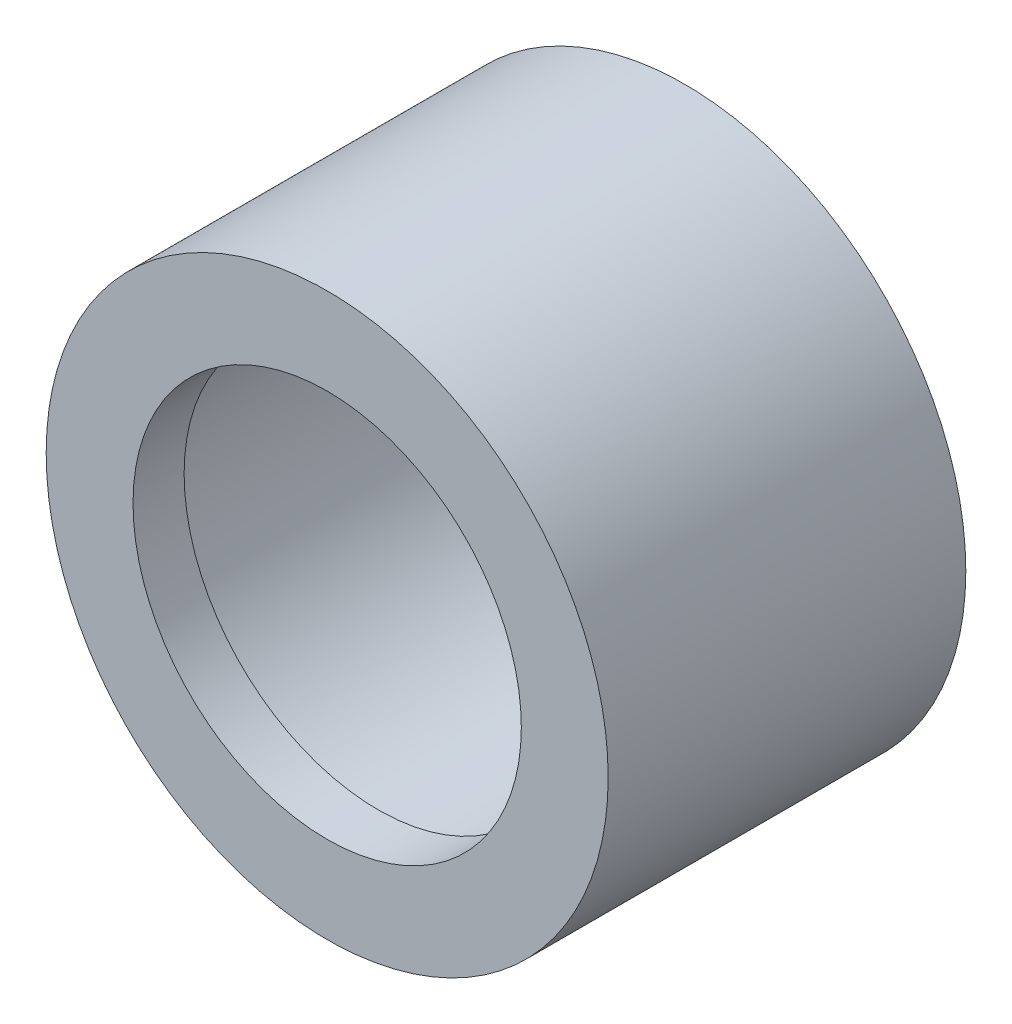
SolidWorks part; units mm, degrees
ref_plane "前视基准面" through (0, 0, 0) normal (0, 0, 1) x (1, 0, 0)
ref_plane "上视基准面" through (0, 0, 0) normal (0, 1, 0) x (1, 0, 0)
ref_plane "右视基准面" through (0, 0, 0) normal (1, 0, 0) x (0, 0, -1)
sketch "草图1" plane through (0, 0, 0) normal (0, 0, 1) x (1, 0, 0)
  circle A0 centre (0, 0) radius 27.5
  dimension "D1" = 55
extrude "拉伸1" add sketch "草图1" along normal blind 3
sketch "草图2" plane through (0, 0, 3) normal (0, 0, 1) x (1, 0, 0)
  circle A0 centre (0, 0) radius 27.5
  dimension "D1" = 55
extrude "拉伸2" add sketch "草图2" along normal blind 32
sketch "草图3" plane through (0, 0, 0) normal (0, 0, -1) x (-1, 0, 0)
  circle A0 centre (0, 0) radius 21
  dimension "D1" = 42
extrude "切除-拉伸1" cut sketch "草图3" against normal blind 30
sketch "草图4" plane through (0, 0, 30) normal (0, 0, -1) x (-1, 0, 0)
  circle A0 centre (0, 0) radius 19
extrude "切除-拉伸2" cut sketch "草图4" against normal blind 30
sketch "草图5" plane through (0, 0, 0) normal (0, 0, -1) x (-1, 0, 0)
  circle A0 centre (0, 0) radius 25
extrude "切除-拉伸3" cut sketch "草图5" against normal blind 3.5
